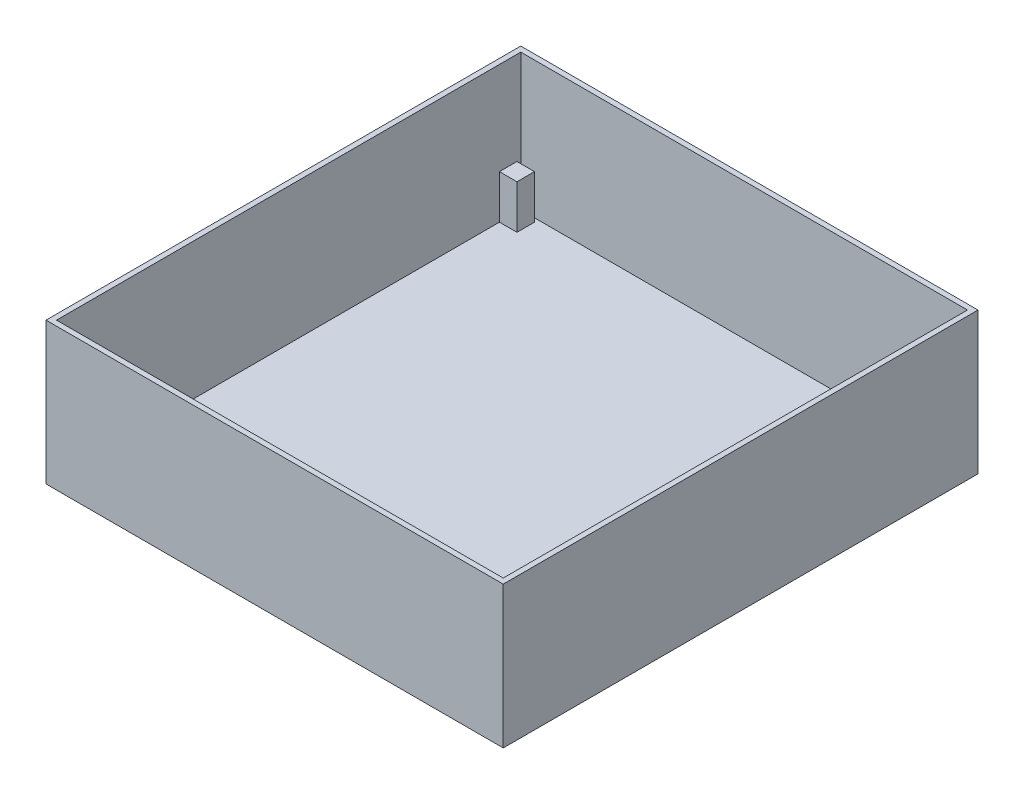
SolidWorks part; units mm, degrees
ref_plane "前视基准面" through (0, 0, 0) normal (0, 0, 1) x (1, 0, 0)
ref_plane "上视基准面" through (0, 0, 0) normal (0, 1, 0) x (1, 0, 0)
ref_plane "右视基准面" through (0, 0, 0) normal (1, 0, 0) x (0, 0, -1)
sketch "草图1" plane through (0, 0, 0) normal (0, 1, 0) x (1, 0, 0)
  line L1 (52.2, 54.2) -> (-52.2, 54.2)
  line L2 (52.2, 54.2) -> (52.2, -54.2)
  line L3 (52.2, -54.2) -> (-52.2, -54.2)
  line L4 (-52.2, 54.2) -> (-52.2, -54.2)
  line L5 (0, -54.2) -> (0, 54.2) construction
  line L6 (52.2, 0) -> (-52.2, 0) construction
  point P0 (0, 0)
  dimension "D1" = 108.4
  dimension "D2" = 104.4
extrude "凸台-拉伸1" add sketch "草图1" along normal blind 32.4
sketch "草图2" plane through (0, 32.4, 0) normal (0, 1, 0) x (1, 0, 0)
  line L1 (51, -53) -> (-51, -53)
  line L2 (51, -53) -> (51, 53)
  line L3 (51, 53) -> (-51, 53)
  line L4 (-51, -53) -> (-51, 53)
  line L5 (0, 53) -> (0, -53) construction
  line L6 (51, 0) -> (-51, 0) construction
  line L8 (-52.2, 54.2) -> (-52.2, -54.2) construction
  line L9 (-52.2, -54.2) -> (52.2, -54.2) construction
  point P0 (0, 0)
  dimension "D1" = 102
  dimension "D2" = 106
  dimension "D3" = 1.2
  dimension "D4" = 1.2
extrude "切除-拉伸1" cut sketch "草图2" against normal blind 31.2
sketch "草图3" plane through (0, 1.2, 0) normal (0, 1, 0) x (1, 0, 0)
  line L0 (51, -53) -> (51, 53) construction
  line L2 (51, -53) -> (51, -52.5406)
  line L3 (51, -53) -> (48, -53)
  line L4 (51, -53) -> (51, -50)
  line L5 (51, -50) -> (48, -50)
  line L6 (48, -53) -> (48, -50)
  line M7 (-51, -53) -> (51, -53)
  line M8 (51, -53) -> (51, 53)
  dimension "D1" = 3
  dimension "D2" = 3
extrude "凸台-拉伸2" add sketch "草图3" along normal blind 10 contours L6 L5 M7 M8
sketch "草图6" plane through (0, 1.2, 0) normal (0, 1, 0) x (1, 0, 0)
  line L1 (51, 53) -> (47, 53)
  line L2 (51, 53) -> (51, 49)
  line L3 (51, 49) -> (47, 49)
  line L4 (47, 53) -> (47, 49)
  dimension "D1" = 4
  dimension "D2" = 4
extrude "凸台-拉伸3" add sketch "草图6" along normal blind 10
sketch "草图7" plane through (0, 1.2, 0) normal (0, 1, 0) x (1, 0, 0)
  line L1 (-51, -53) -> (-47, -53)
  line L2 (-51, -53) -> (-51, -49)
  line L3 (-51, -49) -> (-47, -49)
  line L4 (-47, -53) -> (-47, -49)
  dimension "D1" = 4
  dimension "D2" = 4
extrude "凸台-拉伸4" add sketch "草图7" along normal blind 10
sketch "草图10" plane through (0, 1.2, 0) normal (0, 1, 0) x (1, 0, 0)
  line L0 (-51, 53) -> (-51, -49) construction
  line L1 (-51, 52.1306) -> (-47, 52.1306)
  line L2 (-51, 52.1306) -> (-51, 48.1306)
  line L3 (-51, 48.1306) -> (-47, 48.1306)
  line L4 (-47, 52.1306) -> (-47, 48.1306)
  dimension "D1" = 4
  dimension "D2" = 4
extrude "凸台-拉伸5" add sketch "草图10" along normal blind 10
